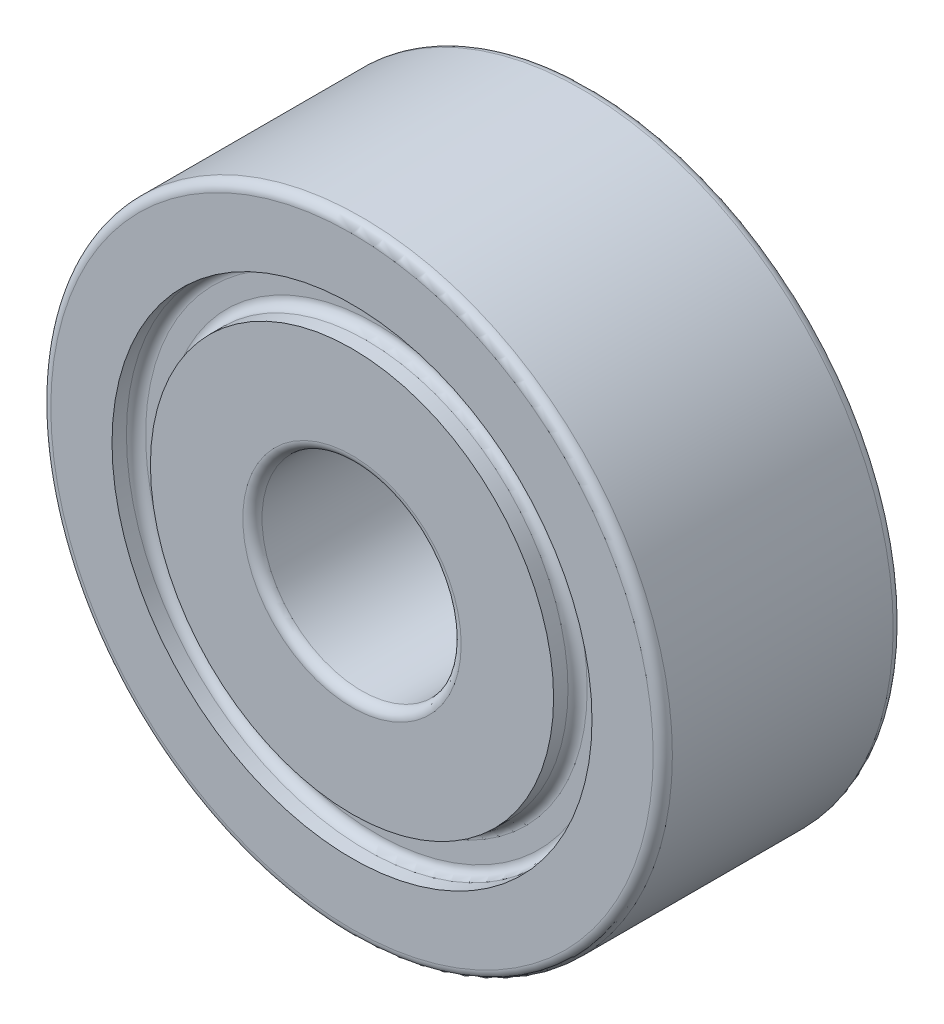
SolidWorks part; units mm, degrees
ref_plane "Front Plane" through (0, 0, 0) normal (0, 0, 1) x (1, 0, 0)
ref_plane "Top Plane" through (0, 0, 0) normal (0, 1, 0) x (1, 0, 0)
ref_plane "Right Plane" through (0, 0, 0) normal (1, 0, 0) x (0, 0, -1)
sketch "Sketch1" plane through (0, 0, 0) normal (0, 0, 1) x (1, 0, 0)
  circle A0 centre (0, 0) radius 6.475
  dimension "D1" = 12.95
extrude "Boss-Extrude1" add sketch "Sketch1" along normal blind 5
sketch "Sketch2" plane through (0, 0, 5) normal (0, 0, 1) x (1, 0, 0)
  circle A0 centre (0, 0) radius 2.075
  dimension "D1" = 4.15
extrude "Cut-Extrude1" cut sketch "Sketch2" against normal through all
sketch "Sketch3" plane through (0, 0, 5) normal (0, 0, 1) x (1, 0, 0)
  line L0 (0, -2.75) -> (0, 2.75) construction
  circle A0 centre (0, 0) radius 4.2
  circle A1 centre (0, 0) radius 5
  dimension "D1" = 8.4
  dimension "D2" = 0.8
extrude "Cut-Extrude2" cut sketch "Sketch3" against normal blind 0.5 contours A1 | A0
fillet "Fillet1" radius 0.2 2 edges at (5, 0, 4.5) (4.2, 0, 4.5)
sketch "Sketch4" plane through (0, 0, 0) normal (0, 0, -1) x (-1, 0, 0)
  circle A0 centre (0, 0) radius 4.2
  circle A1 centre (0, 0) radius 5
  dimension "D1" = 8.4
  dimension "D2" = 0.8
extrude "Cut-Extrude3" cut sketch "Sketch4" against normal blind 0.5 contours A1 | A0
fillet "Fillet2" radius 0.2 2 edges at (-5, 0, 0.5) (-4.2, 0, 0.5)
fillet "Fillet3" radius 0.2 4 edges at (2.075, 0, 5) (2.075, 0, 0) (6.475, 0, 5) (6.475, 0, 0)
